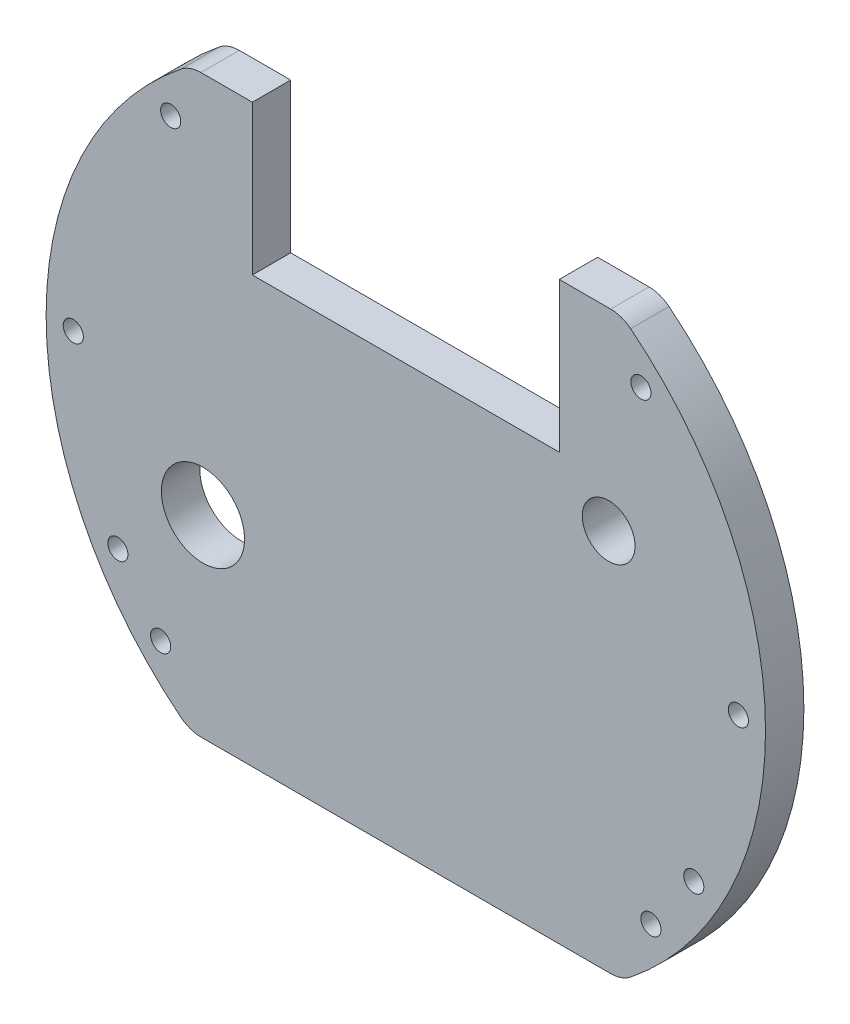
SolidWorks part; units mm, degrees
material "ABS PC"
ref_plane "Ön Düzlem" through (0, 0, 0) normal (0, 0, 1) x (1, 0, 0)
ref_plane "Üst Düzlem" through (0, 0, 0) normal (0, 1, 0) x (1, 0, 0)
ref_plane "Sağ Düzlem" through (0, 0, 0) normal (1, 0, 0) x (0, 0, -1)
sketch "Çizim1" plane through (0, 0, 0) normal (0, 0, 1) x (1, 0, 0)
  line L0 (0, 0) -> (0, 21.6) construction
  line L1 (0, 0) -> (0, -45) construction
  line L2 (32.04, 45) -> (24, 45)
  line L3 (32.04, -45) -> (-32.04, -45)
  line L5 (24, 21.6) -> (-24, 21.6)
  line L6 (-24, 21.6) -> (-24, 45)
  line L7 (24, 21.6) -> (24, 45)
  line L8 (-24, 45) -> (-32.04, 45)
  arc A0 (-35.1659, 43.9024) -> (-35.1659, -43.9024) centre (0, 0) ccw
  arc A1 (35.1659, -43.9024) -> (35.1659, 43.9024) centre (0, 0) ccw
  arc A2 (-32.04, -45) -> (-35.1659, -43.9024) centre (-32.04, -40) cw
  arc A3 (32.04, -45) -> (35.1659, -43.9024) centre (32.04, -40) ccw
  arc A4 (32.04, 45) -> (35.1659, 43.9024) centre (32.04, 40) cw
  arc A5 (-32.04, 45) -> (-35.1659, 43.9024) centre (-32.04, 40) ccw
  point P11 (0, -45)
  point P22 (0, 21.6)
  dimension "D1" = 112.5
  dimension "D3" = 5
  dimension "D2" = 23.4
  dimension "D5" = 48
extrude "Yükseklik-Ekstrüzyon1" add sketch "Çizim1" along normal blind 6
sketch "Çizim2" plane through (0, 0, 0) normal (0, 0, -1) x (-1, 0, 0)
  line L0 (0, 0) -> (-52, 0) construction
  line L1 (0, 0) -> (-36.7696, 36.7696) construction
  line L2 (0, 0) -> (-45.0333, -26) construction
  line L3 (0, 0) -> (36.7696, 36.7696) construction
  line L4 (0, 0) -> (52, 0) construction
  line L5 (0, 0) -> (45.0333, -26) construction
  line L6 (0, 0) -> (-38.3384, -35.1307) construction
  line L8 (0, 0) -> (38.3384, -35.1307) construction
  arc A0 (-36.7696, 36.7696) -> (-45.0333, -26) centre (0, 0) ccw construction
  arc A1 (45.0333, -26) -> (36.7696, 36.7696) centre (0, 0) ccw construction
  arc A2 (-36.7696, 36.7696) -> (-38.3384, -35.1307) centre (0, 0) ccw construction
  arc A3 (38.3384, -35.1307) -> (36.7696, 36.7696) centre (0, 0) ccw construction
  point P3 (52, 0)
  point P4 (-52, 0)
  point P5 (-36.7696, 36.7696)
  point P6 (-45.0333, -26)
  point P7 (36.7696, 36.7696)
  point P9 (45.0333, -26)
  point P12 (-36.7696, 36.7696)
  point P16 (-52, 0)
  point P20 (-45.0333, -26)
  point P24 (45.0333, -26)
  point P28 (52, 0)
  point P32 (36.7696, 36.7696)
  point P40 (-38.3384, -35.1307)
  point P44 (38.3384, -35.1307)
  point P50 (-38.3384, -35.1307)
  point P54 (38.3384, -35.1307)
  dimension "D1" = 104
  dimension "D2" = 45
  dimension "D3" = 30
  dimension "D4" = 45
  dimension "D5" = 30
  dimension "D6" = 42.5
  dimension "D7" = 42.5
hole_wizard "M3x0.5 Helisarmal İçin Dişli Delik1" positions "Çizim2" profile "Çizim4" tap size "M3x0.5" standard "Helicoil® Metric"
sketch "Çizim4" plane through (-38.3384, -35.1307, 0) normal (1, 0, 0) x (0, 1, 0)
  line L0 (0, 0) -> (0, 8.4464)
  line L1 (0, 8.4464) -> (1.575, 7.5)
  line L2 (1.575, 7.5) -> (1.575, 0)
  line L5 (1.575, 0) -> (0, 0)
  line L10 (0, 8.4464) -> (-1.575, 7.5) construction
  line L11 (0, -6.35) -> (0, 107.95) construction
  dimension "Tap Drill Dia." = 3.15
  dimension "Tap Drill Depth" = 7.5
  dimension "Drill Angle" = 118
sketch "Çizim5" plane through (0, 0, 0) normal (0, 0, -1) x (-1, 0, 0)
  line L0 (0, 0) -> (-28.4458, 0) construction
  line L1 (0, 0) -> (-31.7208, 14.7916) construction
  point P4 (-31.7208, 14.7916)
  point P9 (-31.7208, 14.7916)
  dimension "D1" = 25
  dimension "D2" = 35
hole_wizard "M8x1.0 Helisarmal İçin Dişli Delik2" positions "Çizim5" profile "Çizim6" tap size "M8x1.0" standard "Helicoil® Metric"
sketch "Çizim6" plane through (31.7208, 14.7916, 0) normal (1, 0, 0) x (0, 1, 0)
  line L0 (0, 0) -> (0, 20.4786)
  line L1 (0, 20.4786) -> (4.125, 18)
  line L2 (4.125, 18) -> (4.125, 0)
  line L5 (4.125, 0) -> (0, 0)
  line L10 (0, 20.4786) -> (-4.125, 18) construction
  line L11 (0, -6.35) -> (0, 107.95) construction
  dimension "Tap Drill Dia." = 8.25
  dimension "Tap Drill Depth" = 18
  dimension "Drill Angle" = 118
sketch "Çizim7" plane through (0, 0, 0) normal (0, 0, -1) x (-1, 0, 0)
  line L0 (0, 0) -> (31.7208, -14.7916) construction
  line L2 (0, 0) -> (-31.7208, 14.7916) construction
  circle A0 centre (31.7208, -14.7916) radius 6.5
  dimension "D3" = 13
  dimension "D1" = 180
  dimension "D2" = 35
extrude "Kes-Ekstrüzyon1" cut sketch "Çizim7" against normal blind 10
